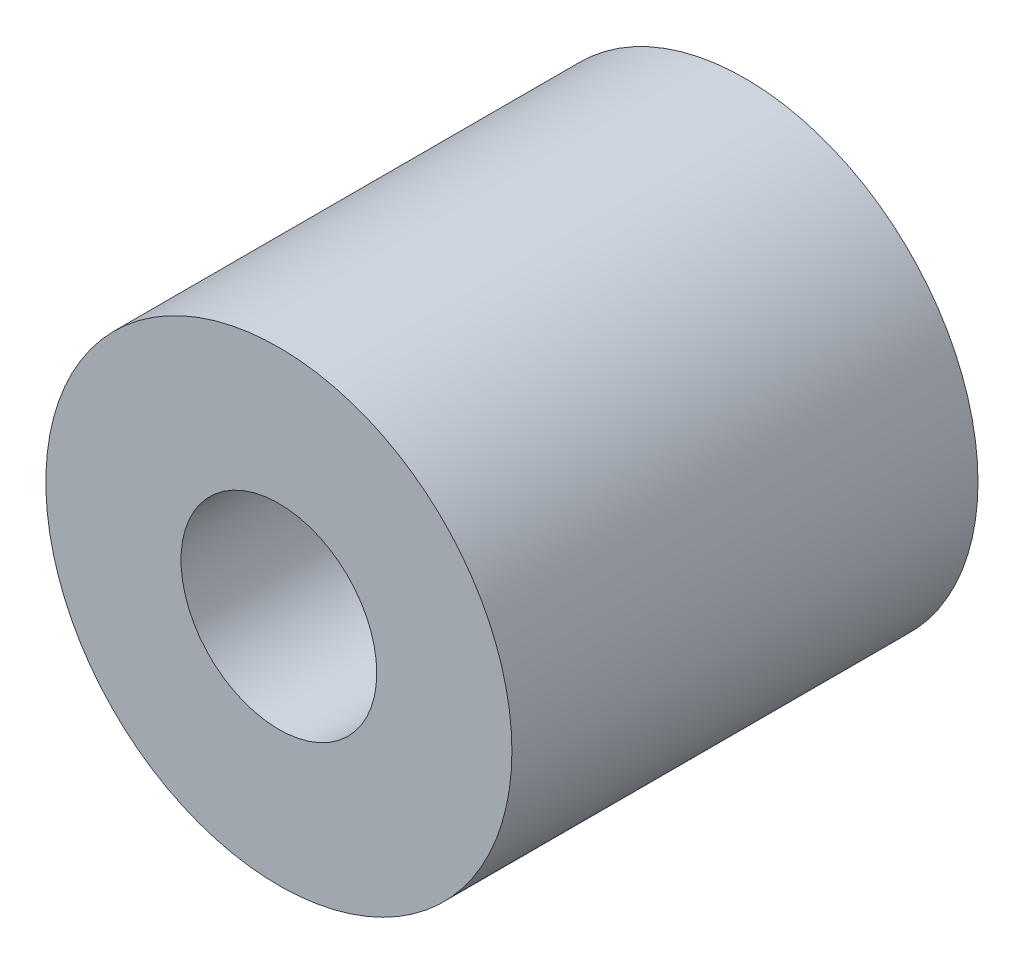
SolidWorks part; units mm, degrees
material "ABS"
ref_plane "前基準面" through (0, 0, 0) normal (0, 0, 1) x (1, 0, 0)
ref_plane "上基準面" through (0, 0, 0) normal (0, 1, 0) x (1, 0, 0)
ref_plane "右基準面" through (0, 0, 0) normal (1, 0, 0) x (0, 0, -1)
sketch "草圖1" plane through (0, 0, 0) normal (0, 0, 1) x (1, 0, 0)
  circle A0 centre (0, 0) radius 5
  circle A1 centre (0, 0) radius 2.1
  dimension "D1" = 4.2
  dimension "D2" = 10
extrude "填料-伸長1" add sketch "草圖1" along normal blind 10
